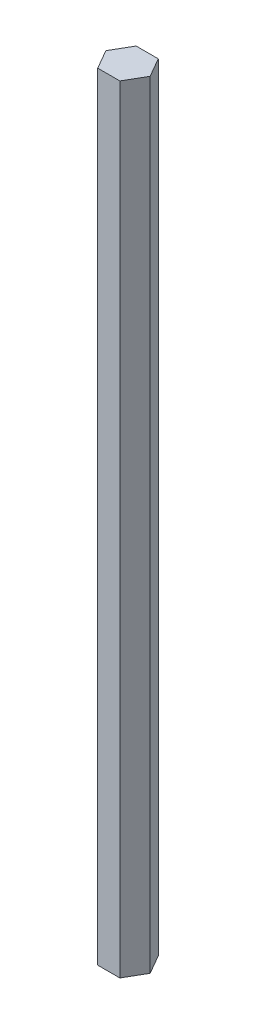
SolidWorks part; units mm, degrees
ref_plane "Front Plane" through (0, 0, 0) normal (0, 0, 1) x (1, 0, 0)
ref_plane "Top Plane" through (0, 0, 0) normal (0, 1, 0) x (1, 0, 0)
ref_plane "Right Plane" through (0, 0, 0) normal (1, 0, 0) x (0, 0, -1)
sketch "Sketch1" plane through (0, 0, 0) normal (0, 1, 0) x (1, 0, 0)
  line L1 (3, 0) -> (1.5, 2.5981)
  line L2 (1.5, 2.5981) -> (-1.5, 2.5981)
  line L3 (-1.5, 2.5981) -> (-3, 0)
  line L4 (-3, 0) -> (-1.5, -2.5981)
  line L5 (-1.5, -2.5981) -> (1.5, -2.5981)
  line L6 (1.5, -2.5981) -> (3, 0)
  circle A0 centre (0, 0) radius 2.5981 construction
  dimension "D1" = 3
extrude "Boss-Extrude1" add sketch "Sketch1" along normal blind 105.2
sketch "Sketch3" plane through (0, 0, 0) normal (0, -1, 0) x (1, 0, 0)
  circle A0 centre (0, 0) radius 1.6
  dimension "D1" = 3.2
extrude "Cut-Extrude1" cut sketch "Sketch3" against normal blind 5
